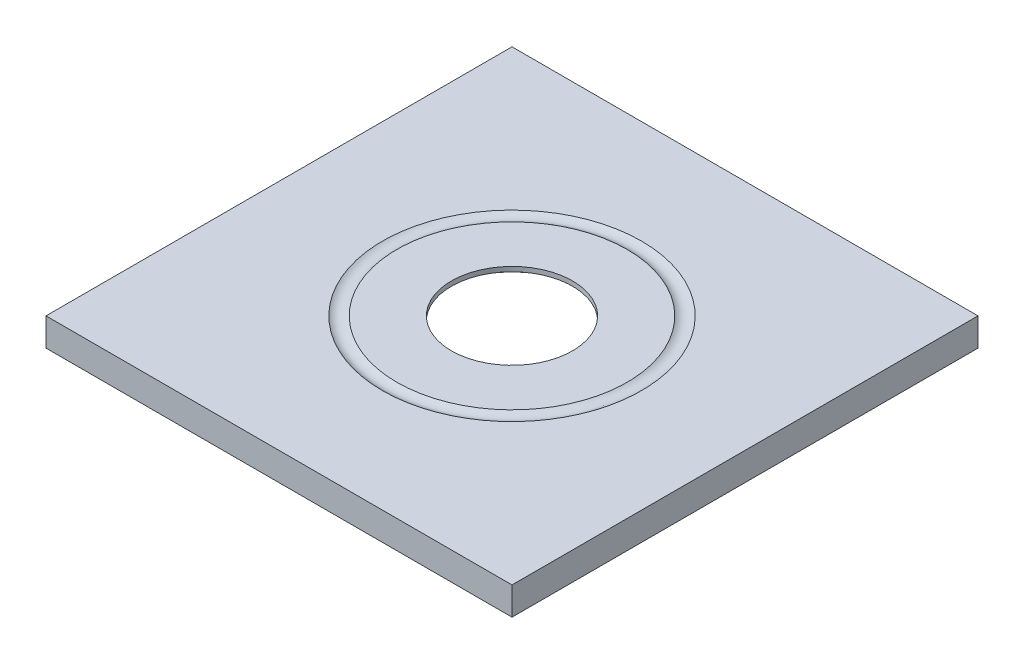
SolidWorks part; units mm, degrees
material "ABS"
ref_plane "Front Plane" through (0, 0, 0) normal (0, 0, 1) x (1, 0, 0)
ref_plane "Top Plane" through (0, 0, 0) normal (0, 1, 0) x (1, 0, 0)
ref_plane "Right Plane" through (0, 0, 0) normal (1, 0, 0) x (0, 0, -1)
ref_plane "Plane1" through (0, 0, 0) normal (0, 0, -1) x (-1, 0, 0)
sketch "Sketch1" plane through (0, 0, 0) normal (0, 0, -1) x (-1, 0, 0)
  line L7 (0, 0) -> (0, 6.8724) construction
  line L23 (-40, 4) -> (-40, -8)
  line L25 (-60, -8) -> (-60, 4)
  line L26 (-60, 4) -> (-55.5957, 4)
  line L27 (-49.4043, 4) -> (-40, 4)
  line L28 (-40, -8) -> (-49.4043, -8)
  line L29 (-55.5957, -8) -> (-60, -8)
  arc A0 (-49.4043, -8) -> (-55.5957, -8) centre (-52.5, -12.1157) ccw
  arc A1 (-49.4043, 4) -> (-55.5957, 4) centre (-52.5, 8.1157) cw
  dimension "D1" = 5.15
  dimension "D2" = 12
  dimension "D3" = 6.1914
revolve "Revolve1" add sketch "Sketch1" angle 360 about L7
sketch "Sketch2" plane through (0, 4, 0) normal (0, 1, 0) x (1, 0, 0)
  line L1 (-100, 100) -> (100, 100)
  line L2 (-100, 100) -> (-100, -100)
  line L3 (-100, -100) -> (100, -100)
  line L4 (100, 100) -> (100, -100)
  circle A2 centre (0, 0) radius 60
  point P0 (0, 0)
  dimension "D1" = 100
  dimension "D2" = 100
  dimension "D3" = 100
  dimension "D4" = 100
extrude "Boss-Extrude1" add sketch "Sketch2" against normal blind 12
sketch "Sketch3" plane through (0, 4, 0) normal (0, 1, 0) x (1, 0, 0)
  circle A0 centre (0, 0) radius 40
  circle A1 centre (0, 0) radius 26
  dimension "D1" = 52
extrude "Boss-Extrude2" add sketch "Sketch3" against normal blind 2
